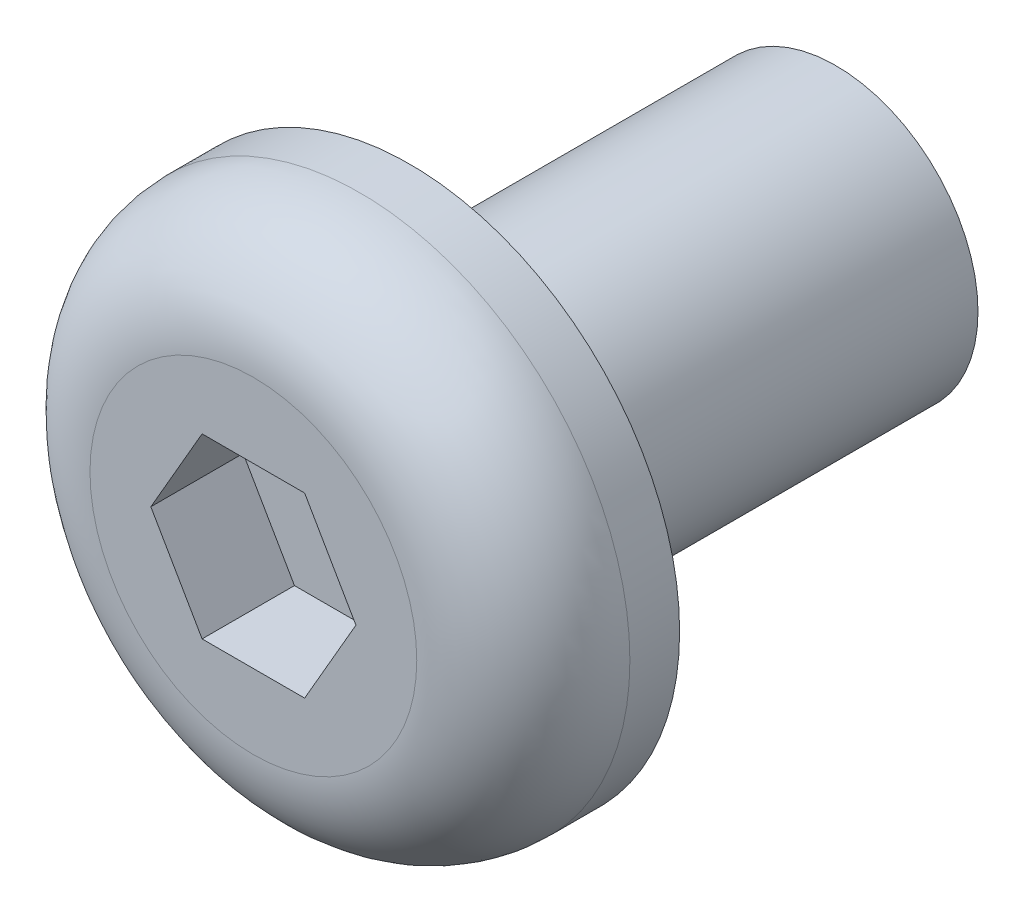
SolidWorks part; units mm, degrees
ref_plane "Front Plane" through (0, 0, 0) normal (0, 0, 1) x (1, 0, 0)
ref_plane "Top Plane" through (0, 0, 0) normal (0, 1, 0) x (1, 0, 0)
ref_plane "Right Plane" through (0, 0, 0) normal (1, 0, 0) x (0, 0, -1)
sketch "Sketch1" plane through (0, 0, 0) normal (0, 0, 1) x (1, 0, 0)
  circle A0 centre (0, 0) radius 2
extrude "Shank" add sketch "Sketch1" along normal blind 6
ref_plane "Plane_z6" through (0, 0, 6) normal (0, 0, 1) x (1, 0, 0)
sketch "Sketch2" plane through (0, 0, 6) normal (0, 0, 1) x (1, 0, 0)
  circle A0 centre (0, 0) radius 3.8
extrude "Head" add sketch "Sketch2" along normal blind 2.2
fillet "Button_round" radius 1.5 1 edges at (3.8, 0, 8.2)
ref_plane "Plane_z6_9" through (0, 0, 6.9) normal (0, 0, 1) x (1, 0, 0)
sketch "Sketch3" plane through (0, 0, 6.9) normal (0, 0, 1) x (1, 0, 0)
  line L0 (1.4434, 0) -> (0.7217, 1.25)
  line L1 (0.7217, 1.25) -> (-0.7217, 1.25)
  line L2 (-0.7217, 1.25) -> (-1.4434, 0)
  line L3 (-1.4434, 0) -> (-0.7217, -1.25)
  line L4 (-0.7217, -1.25) -> (0.7217, -1.25)
  line L5 (0.7217, -1.25) -> (1.4434, 0)
extrude "Socket" cut sketch "Sketch3" along normal blind 1.3
